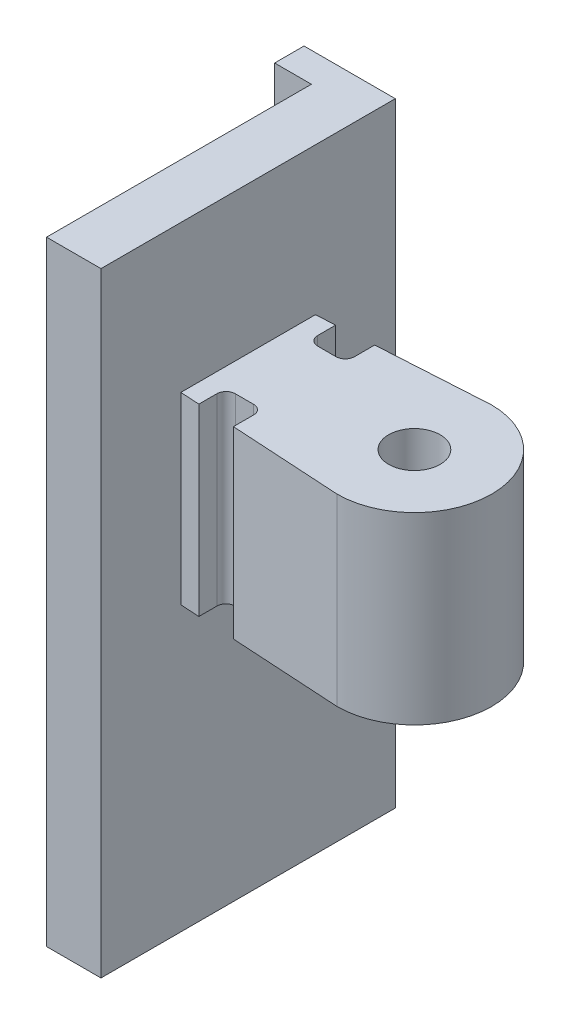
SolidWorks part; units mm, degrees
ref_plane "Front Plane" through (0, 0, 0) normal (0, 0, 1) x (1, 0, 0)
ref_plane "Top Plane" through (0, 0, 0) normal (0, 1, 0) x (1, 0, 0)
ref_plane "Right Plane" through (0, 0, 0) normal (1, 0, 0) x (0, 0, -1)
sketch "Sketch3" plane through (0, 0, 0) normal (0, 1, 0) x (1, 0, 0)
  line L0 (-5, 0.75) -> (0, 1.05) construction
  line L3 (0, -1.05) -> (-5, -0.75) construction
  line L4 (-2.5, 0.9) -> (-2, 0.93)
  line L6 (-4.25, 0) -> (-5.75, 0) construction
  line L7 (-2, 0.93) -> (-2, 0.56)
  line L8 (-2.5, 0.9) -> (-5, 0.9) construction
  line L9 (-2.5, 0.9) -> (-2.5, -0.9)
  line L10 (-2.5, -0.9) -> (-5, -0.9) construction
  line L11 (-5, 0.9) -> (-5, -0.9) construction
  line L12 (-2, 0.96) -> (-1.5, 0.96) construction
  line L13 (-2, 0.96) -> (-2, 0.56) construction
  line L14 (-2, 0.56) -> (-1.5, 0.56)
  line L15 (-1.5, 0.96) -> (-1.5, 0.56)
  line L16 (-1.5, -0.56) -> (-2, -0.56)
  line L17 (-1.5, -0.56) -> (-1.5, -0.96)
  line L18 (-1.5, -0.96) -> (-2, -0.96) construction
  line L19 (-2, -0.56) -> (-2, -0.96) construction
  line L21 (-2.5, -0.9) -> (-2, -0.93)
  line L22 (-2, -0.93) -> (-2, -0.56)
  line L23 (-1.5, 0.96) -> (0, 1.05)
  line L24 (0, -1.05) -> (-1.5, -0.96)
  circle A2 centre (0, 0) radius 0.6 construction
  circle A3 centre (0, 0) radius 0.4 construction
  circle A4 centre (-5, 0) radius 0.35 construction
  circle A5 centre (0, 0) radius 1.05 construction
  circle A6 centre (-5, 0) radius 0.75 construction
  arc A7 (-5, 0.9) -> (-5, -0.9) centre (-5, 0) ccw construction
  arc A8 (0, 1.05) -> (0, -1.05) centre (0, 0) cw
  point P4 (-2, -0.93)
  point P15 (-5, 0)
  point P16 (-2, 0.93)
  point P22 (-5, 0)
  dimension "D2" = 1.2
  dimension "D3" = 0.8
  dimension "D4" = 0.7
  dimension "D6" = 5
  dimension "D1" = 1.5
  dimension "D5" = 2.1
  dimension "D7" = 0.4
  dimension "D9" = 2.5
  dimension "D10" = 1.8
  dimension "D11" = 2.5
  dimension "D12" = 0.5
  dimension "D14" = 1.5
extrude "Boss-Extrude1" add sketch "Sketch3" along normal blind 2.5 contours L21 L22 L16 L17 L24 A8 L23 L15 L14 L7 L4 L9
sketch "Sketch4" plane through (0, 2.5, 0) normal (0, 1, 0) x (1, 0, 0)
  circle A0 centre (0, 0) radius 0.35
  point P9 (0, 0)
  dimension "D1" = 0.7
extrude "Through Holes" cut sketch "Sketch4" against normal through all contours A0
fillet "Fillet1" radius 0.125 4 edges at (-2, 1.25, 0.56) (-1.5, 1.25, 0.56) (-1.5, 1.25, -0.56) (-2, 1.25, -0.56)
sketch "Sketch5" plane through (0, 0, 0) normal (0, 1, 0) x (1, 0, 0)
  line L0 (-2.25, 0) -> (1.75, 0) construction
  line L1 (-2.25, -2) -> (1.75, -2)
  line L2 (-2.25, -2) -> (-2.25, 2)
  line L3 (-2.25, 2) -> (1.75, 2)
  line L4 (1.75, -2) -> (1.75, 2)
  line L5 (-2.25, -2) -> (1.75, 2) construction
  line L6 (-2.25, 2) -> (1.75, -2) construction
  circle A1 centre (0, 0) radius 0.125
  point P1 (-0.25, 0)
  dimension "D2" = 0.25
  dimension "D1" = 1.75
  dimension "D3" = 4
sketch "Sketch11" plane through (-2.5, 0, 0) normal (-1, 0, 0) x (0, 0, 1)
  line L0 (0, 2.5) -> (0, 4.5) construction
  line L1 (-2, 4.5) -> (2, 4.5)
  line L2 (-2, 4.5) -> (-2, -3.85)
  line L3 (-2, -3.85) -> (2, -3.85)
  line L4 (2, 4.5) -> (2, -3.85)
  line L5 (-0.9, 2.5) -> (0.9, 2.5) construction
  dimension "D1" = 4
  dimension "D2" = 8.35
  dimension "D3" = 2
extrude "Boss-Extrude4" add sketch "Sketch11" along normal blind 0.5 and the other way blind 0.24
sketch "Sketch12" plane through (-3, 0, 0) normal (-1, 0, 0) x (0, 0, 1)
  line L0 (-2, 4.5) -> (-1.6, 4.5)
  line L1 (2, 4.5) -> (-2, 4.5) construction
  line L2 (-1.6, 4.5) -> (-1.6, -3.85)
  line L3 (-2, -3.85) -> (2, -3.85) construction
  line L4 (-1.6, -3.85) -> (-2, -3.85)
  line L5 (-2, -3.85) -> (-2, 4.5)
  dimension "D1" = 0.4
extrude "Boss-Extrude5" add sketch "Sketch12" along normal blind 0.5
